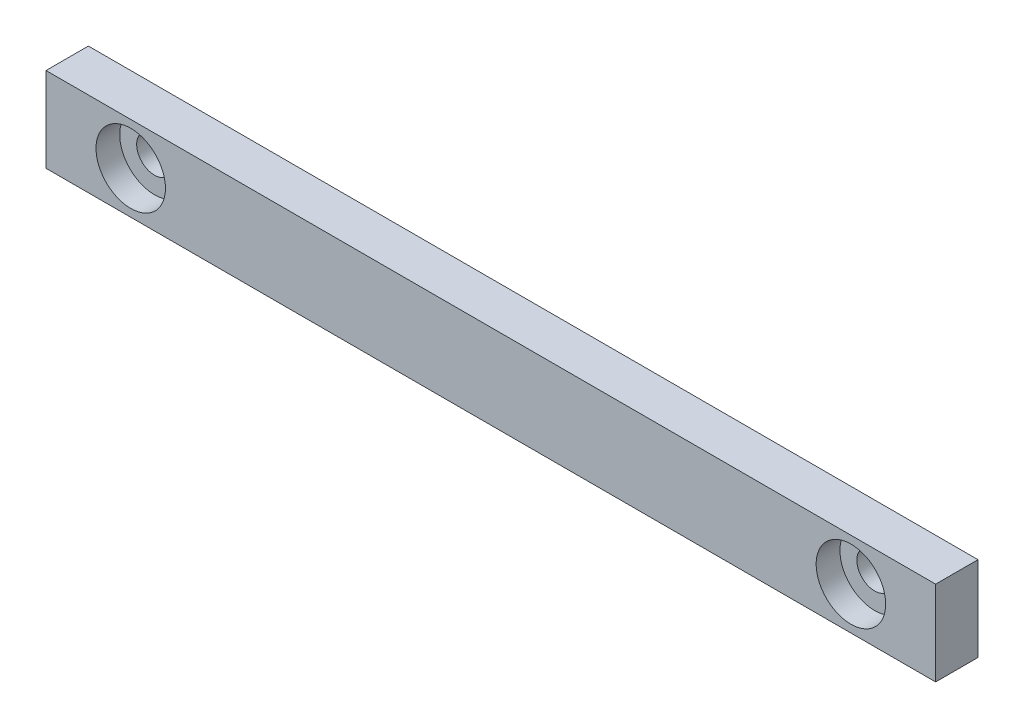
SolidWorks part; units mm, degrees
ref_plane "前基準面" through (0, 0, 0) normal (0, 0, 1) x (1, 0, 0)
ref_plane "上基準面" through (0, 0, 0) normal (0, 1, 0) x (1, 0, 0)
ref_plane "右基準面" through (0, 0, 0) normal (1, 0, 0) x (0, 0, -1)
sketch "草圖1" plane through (0, 0, 0) normal (0, 0, 1) x (1, 0, 0)
  line L1 (-48.6776, 9.9071) -> (56.3224, 9.9071)
  line L2 (-48.6776, 9.9071) -> (-48.6776, -0.0929)
  line L3 (-48.6776, -0.0929) -> (56.3224, -0.0929)
  line L4 (56.3224, 9.9071) -> (56.3224, -0.0929)
  line L5 (3.8224, -0.0929) -> (3.8224, 9.9071) construction
  line L6 (-48.6776, 4.9071) -> (56.3224, 4.9071) construction
  circle A0 centre (-38.6776, 4.9071) radius 2.1
  circle A1 centre (46.3224, 4.9071) radius 2.1
  point P116 (3.8224, 4.9071)
  dimension "D3" = 4.2
  dimension "D4" = 4.2
  dimension "D1" = 105
  dimension "D2" = 10
  dimension "D5" = 10
  dimension "D6" = 10
extrude "填料-伸長1" add sketch "草圖1" along normal blind 5 contours L3 L4 L1 L2 | A0 | A1
sketch "草圖2" plane through (0, 0, 5) normal (0, 0, 1) x (1, 0, 0)
  circle A0 centre (-38.6776, 4.9071) radius 4.1
  circle A1 centre (46.3224, 4.9071) radius 4.1
  dimension "D1" = 8.2
  dimension "D2" = 8.2
extrude "除料-伸長1" cut sketch "草圖2" against normal blind 2.8
